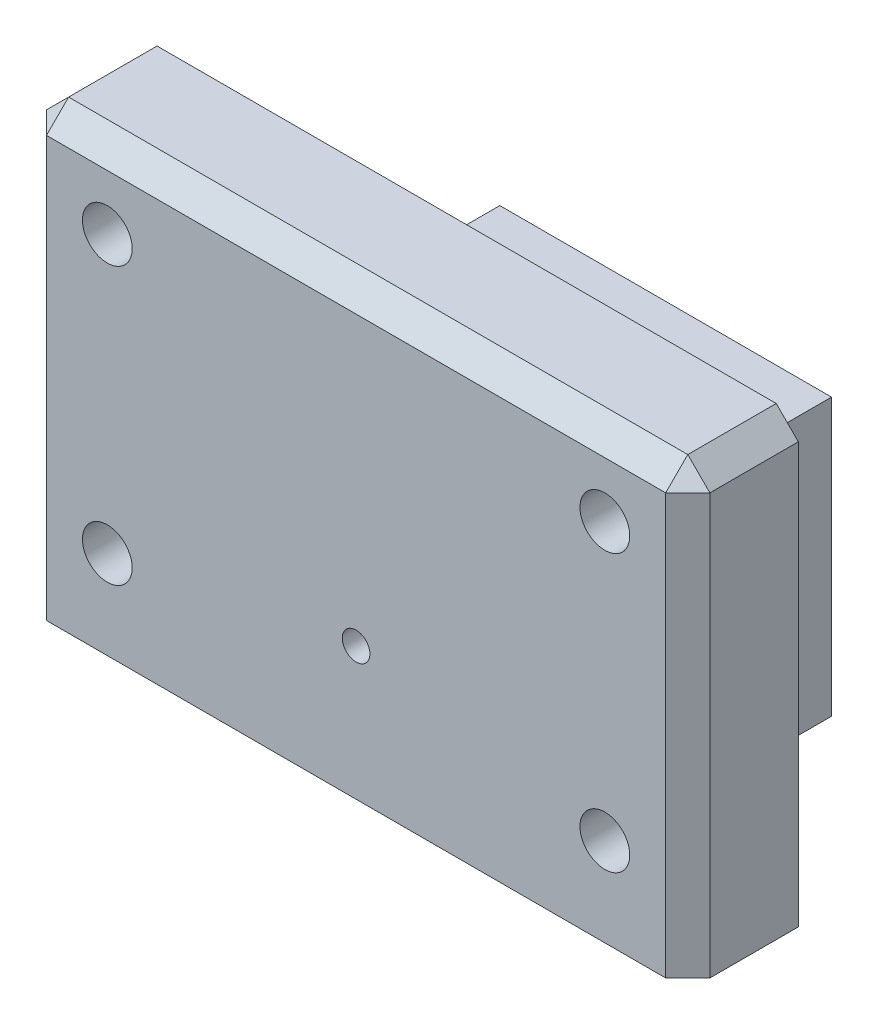
SolidWorks part; units mm, degrees
material "3D printed plastic"
ref_plane "Front Plane" through (0, 0, 0) normal (0, 0, 1) x (1, 0, 0)
ref_plane "Top Plane" through (0, 0, 0) normal (0, 1, 0) x (1, 0, 0)
ref_plane "Right Plane" through (0, 0, 0) normal (1, 0, 0) x (0, 0, -1)
sketch "Sketch1" plane through (0, 0, 0) normal (0, 1, 0) x (1, 0, 0)
  line L0 (-15, -9) -> (-30, -9)
  line L1 (-15, 9) -> (15, 9)
  line L2 (-15, 9) -> (-15, -9)
  line L3 (0, 0) -> (0, 9) construction
  line L4 (15, 9) -> (15, -9)
  line L5 (30, -9) -> (15, -9)
  line L6 (30, -9) -> (30, -19)
  line L7 (30, -19) -> (-30, -19)
  line L8 (-30, -9) -> (-30, -19)
  circle A0 centre (0, 0) radius 4
  dimension "D4" = 8
  dimension "D1" = 30
  dimension "D2" = 18
  dimension "D3" = 9
  dimension "D5" = 60
  dimension "D6" = 10
extrude "Boss-Extrude1" add sketch "Sketch1" along normal mid plane 25
sketch "Sketch2" plane through (0, 12.5, 0) normal (0, 1, 0) x (1, 0, 0)
  line L1 (-30, -9) -> (30, -9)
  line L2 (-30, -9) -> (-30, -19)
  line L3 (-30, -19) -> (30, -19)
  line L4 (30, -9) -> (30, -19)
extrude "Boss-Extrude2" add sketch "Sketch2" along normal blind 15
chamfer "Chamfer1" distance 2 angle 45 5 edges at (30, 7.5, 19) (0, 27.5, 19) (-30, 7.5, 19) (-30, 27.5, 14) (30, 27.5, 14)
sketch "Sketch3" plane through (0, 0, 9) normal (0, 0, -1) x (-1, 0, 0)
  line L0 (22.5, -4.5) -> (22.5, 20.5) construction
  line L1 (22.5, 20.5) -> (-22.5, 20.5) construction
  line L2 (-22.5, 20.5) -> (-22.5, -4.5) construction
  line L3 (-22.5, -4.5) -> (22.5, -4.5) construction
  line L5 (0, -4.5) -> (0, -12.5) construction
  line L6 (-15, -12.5) -> (15, -12.5) construction
  line L7 (15, -12.5) -> (30, -12.5) construction
  circle A0 centre (-22.5, 20.5) radius 2.25
  circle A1 centre (-22.5, -4.5) radius 2.25
  circle A2 centre (22.5, 20.5) radius 2.25
  circle A3 centre (22.5, -4.5) radius 2.25
  point P14 (22.5, -12.5)
  dimension "D4" = 4.5
  dimension "D1" = 45
  dimension "D2" = 25
  dimension "D3" = 8
extrude "Cut-Extrude1" cut sketch "Sketch3" against normal through all
sketch "Sketch4" plane through (0, 0, 19) normal (0, 0, 1) x (1, 0, 0)
  line L0 (0, -0.5) -> (0, -12.5) construction
  line L1 (-28, -12.5) -> (28, -12.5) construction
  circle A0 centre (0, -0.5) radius 1.25
  dimension "D2" = 2.5
  dimension "D1" = 12
extrude "Cut-Extrude2" cut sketch "Sketch4" against normal up to next
